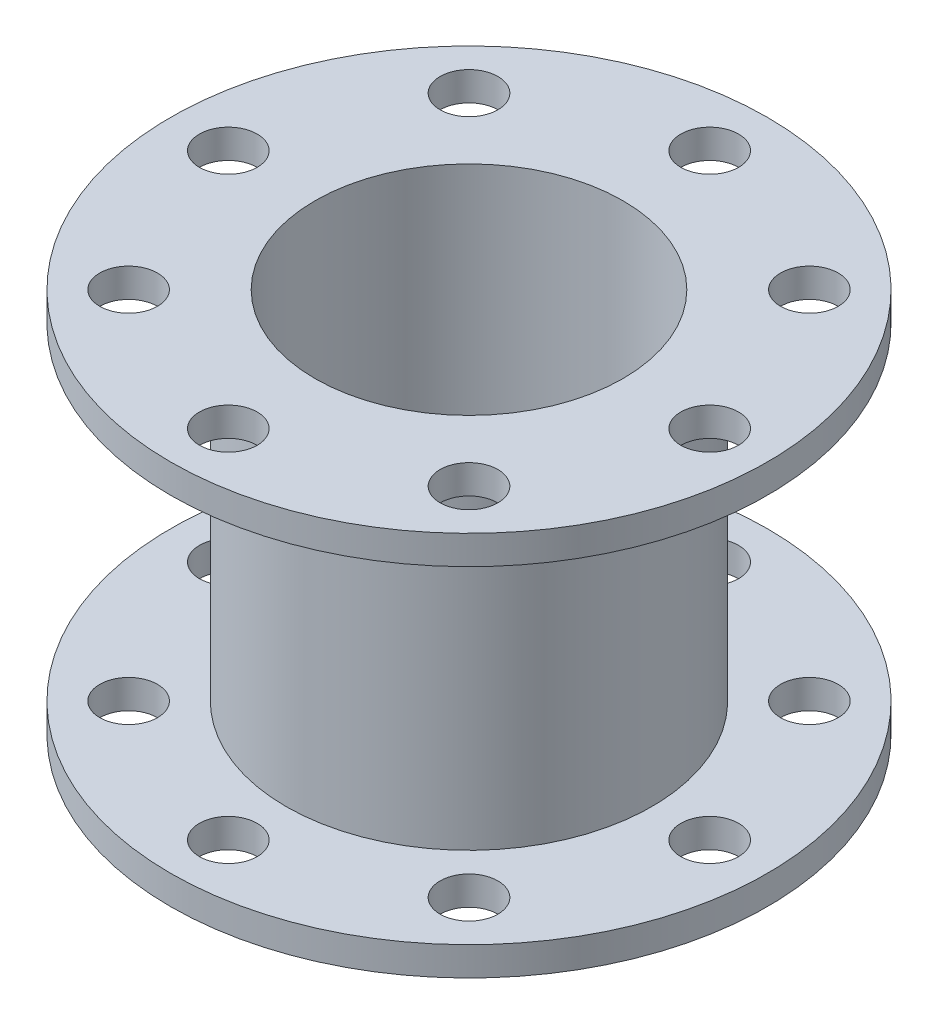
SolidWorks part; units mm, degrees
material "Custom Plastic"
ref_plane "前视基准面" through (0, 0, 0) normal (0, 0, 1) x (1, 0, 0)
ref_plane "上视基准面" through (0, 0, 0) normal (0, 1, 0) x (1, 0, 0)
ref_plane "右视基准面" through (0, 0, 0) normal (1, 0, 0) x (0, 0, -1)
other "Center of Mass"
sketch "Sketch4" plane through (0, 0, 0) normal (0, 0, 1) x (1, 0, 0)
  line L0 (19, 17) -> (19, -17)
  line L1 (19, -17) -> (31, -17)
  line L2 (31, -17) -> (31, -20)
  line L3 (31, -20) -> (16, -20)
  line L4 (16, -20) -> (16, 20)
  line L5 (16, 20) -> (31, 20)
  line L6 (31, 20) -> (31, 17)
  line L7 (31, 17) -> (19, 17)
  line L8 (25, -17) -> (25, 7.9733) construction
  line L9 (0, 0) -> (0, 19.0443) construction
  line L10 (0, 0) -> (32, 0) construction
  point P13 (16, 0)
  dimension "D1" = 3
  dimension "D2" = 3
  dimension "D3" = 25
  dimension "D4" = 12
  dimension "D5" = 12
  dimension "D6" = 3
  dimension "D7" = 40
revolve "Revolve1" add sketch "Sketch4" angle 360 about L9
sketch "Sketch5" plane through (0, -17, 0) normal (0, 1, 0) x (1, 0, 0)
  line L0 (0, 0) -> (25, 0) construction
  circle A0 centre (25, 0) radius 3
  dimension "D1" = 6
  dimension "D2" = 25
extrude "Cut-Extrude2" cut sketch "Sketch5" along normal mid plane 1000
pattern_circular "CirPattern2" count 8 over 360 about axis through (0, 0, 0) along (0, 1, 0) of "Cut-Extrude2"
